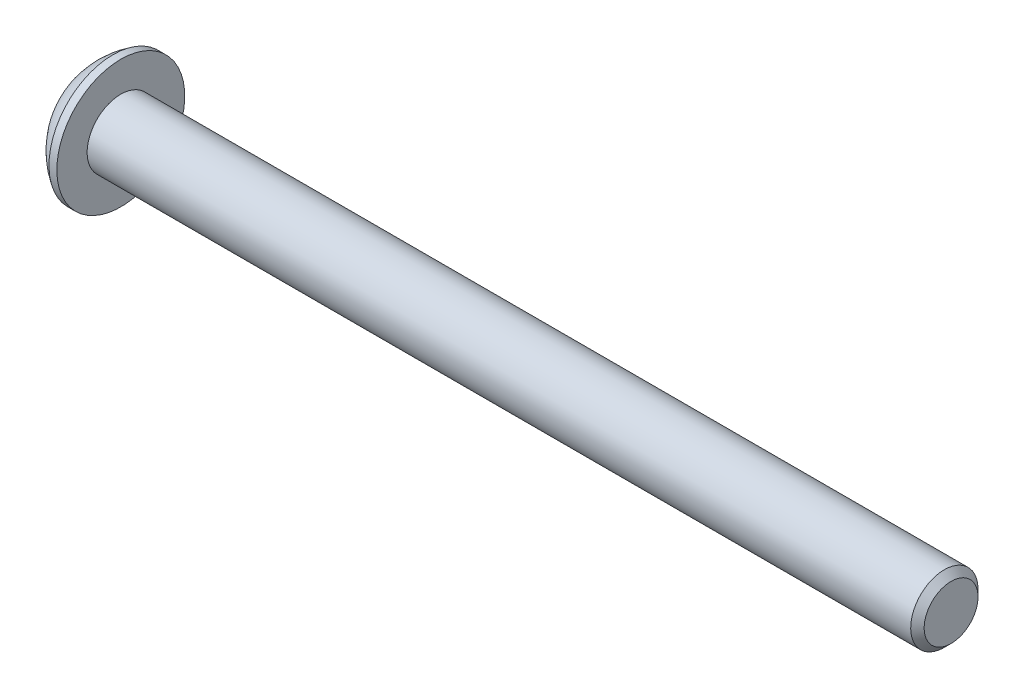
SolidWorks part; units mm, degrees
ref_plane "Front Plane" through (0, 0, 0) normal (0, 0, 1) x (1, 0, 0)
ref_plane "Top Plane" through (0, 0, 0) normal (0, 1, 0) x (1, 0, 0)
ref_plane "Right Plane" through (0, 0, 0) normal (1, 0, 0) x (0, 0, -1)
sketch "Sketch1" plane through (0, 0, 0) normal (0, 0, 1) x (1, 0, 0)
  line L0 (38.65, 0) -> (0, 0)
  line L1 (0, 0) -> (0, 1.425)
  line L2 (1.3, 2.85) -> (1.65, 2.85)
  line L3 (1.65, 2.85) -> (1.65, 1.5)
  line L4 (1.65, 1.5) -> (38.65, 1.5)
  line L5 (38.65, 1.5) -> (38.65, 0)
  arc A1 (1.3, 2.85) -> (0, 1.425) centre (3.1356, -0.13) ccw
  dimension "D5" = 3.5
  dimension "D1" = 37
  dimension "D2" = 2.85
  dimension "D3" = 0.35
  dimension "D4" = 1.65
  dimension "D6" = 1.425
  dimension "D7" = 1.5
revolve "Revolve1" add sketch "Sketch1" angle 360 about L0
chamfer "Chamfer1" distance 0.3 angle 45 1 edges at (38.65, 1.5, 0)
sketch "Sketch2" plane through (0, 0, 0) normal (-1, 0, 0) x (0, 0, 1)
  line L1 (1, 0.5774) -> (0, 1.1547)
  line L2 (0, 1.1547) -> (-1, 0.5774)
  line L3 (-1, 0.5774) -> (-1, -0.5774)
  line L4 (-1, -0.5774) -> (0, -1.1547)
  line L5 (0, -1.1547) -> (1, -0.5774)
  line L6 (1, -0.5774) -> (1, 0.5774)
  circle A0 centre (0, 0) radius 1 construction
  dimension "D1" = 2
extrude "Cut-Extrude1" cut sketch "Sketch2" against normal blind 1
